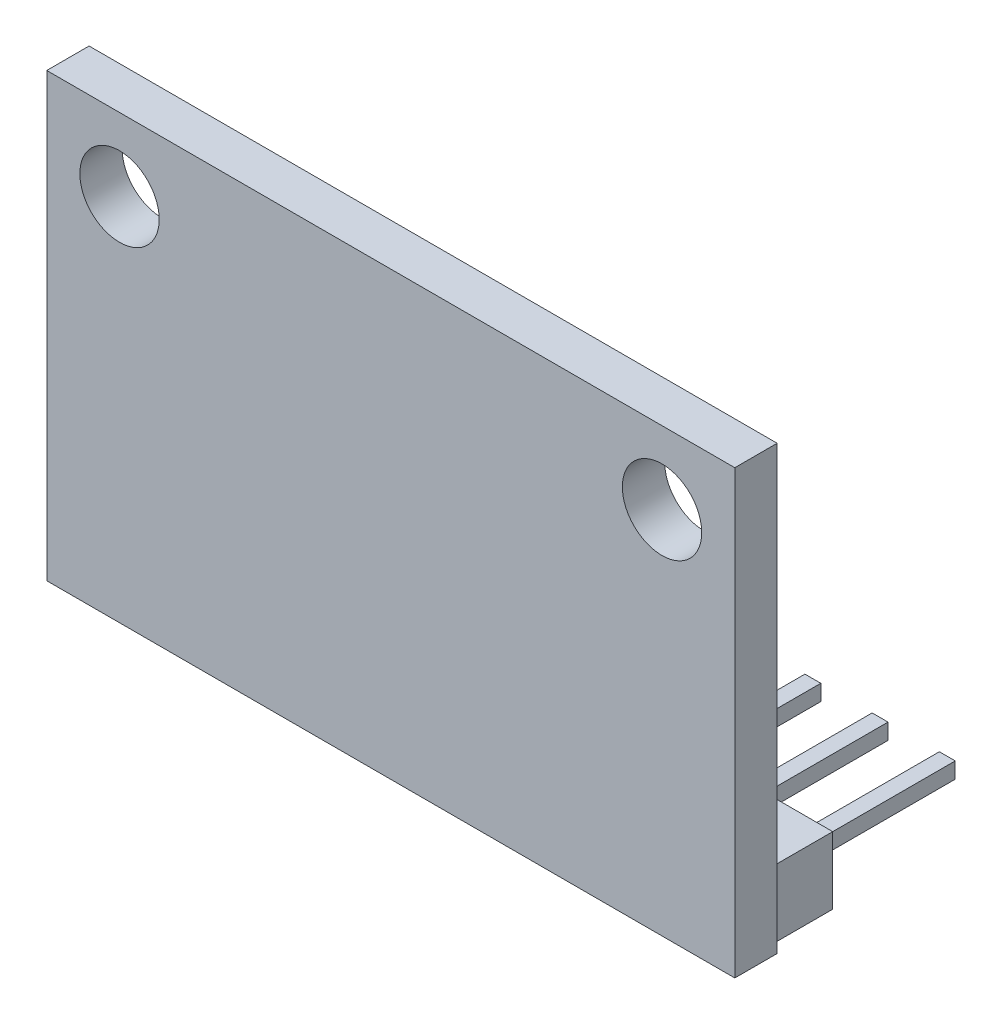
SolidWorks part; units mm, degrees
ref_plane "Ebene vorne" through (0, 0, 0) normal (0, 0, 1) x (1, 0, 0)
ref_plane "Ebene oben" through (0, 0, 0) normal (0, 1, 0) x (1, 0, 0)
ref_plane "Ebene rechts" through (0, 0, 0) normal (1, 0, 0) x (0, 0, -1)
sketch "Skizze1" plane through (0, 0, 0) normal (0, 0, 1) x (1, 0, 0)
  line L1 (-13, -8.35) -> (13, -8.35)
  line L2 (-13, -8.35) -> (-13, 8.35)
  line L3 (-13, 8.35) -> (13, 8.35)
  line L4 (13, -8.35) -> (13, 8.35)
  line L5 (-13, -8.35) -> (13, 8.35) construction
  line L6 (-13, 8.35) -> (13, -8.35) construction
  circle A0 centre (-10.25, 5.6) radius 1.5
  circle A1 centre (10.25, 5.6) radius 1.5
  point P0 (0, 0)
  point P10 (0, 0)
  dimension "D4" = 3
  dimension "D1" = 26
  dimension "D2" = 16.7
  dimension "D3" = 2.75
  dimension "D5" = 2.75
  dimension "D6" = 20.5
extrude "Aufsatz-Linear austragen1" add sketch "Skizze1" along normal blind 1.6
sketch "Skizze3" plane through (0, 0, 0) normal (0, 0, -1) x (-1, 0, 0)
  line L0 (-8.59, -7.28) -> (-8.59, -6.68) construction
  line L1 (-12.7, -8.25) -> (12.7, -8.25)
  line L2 (-12.7, -8.25) -> (-12.7, -5.71)
  line L3 (-12.7, -5.71) -> (12.7, -5.71)
  line L4 (12.7, -8.25) -> (12.7, -5.71)
  line L5 (-11.13, -7.28) -> (-11.73, -7.28) construction
  line L6 (-11.13, -7.28) -> (-11.13, -6.68) construction
  line L7 (-11.13, -6.68) -> (-11.73, -6.68) construction
  line L8 (-11.73, -7.28) -> (-11.73, -6.68) construction
  line L9 (-11.13, -7.28) -> (-11.73, -6.68) construction
  line L10 (-11.13, -6.68) -> (-11.73, -7.28) construction
  line L11 (-8.59, -7.28) -> (-9.19, -7.28) construction
  line L12 (-9.19, -7.28) -> (-9.19, -6.68) construction
  line L13 (-8.59, -6.68) -> (-9.19, -6.68) construction
  line L14 (-6.05, -7.28) -> (-6.05, -6.68) construction
  line L15 (-6.05, -7.28) -> (-6.65, -7.28) construction
  line L16 (-6.65, -7.28) -> (-6.65, -6.68) construction
  line L17 (-6.05, -6.68) -> (-6.65, -6.68) construction
  line L18 (-3.51, -7.28) -> (-3.51, -6.68) construction
  line L19 (-3.51, -7.28) -> (-4.11, -7.28) construction
  line L20 (-4.11, -7.28) -> (-4.11, -6.68) construction
  line L21 (-3.51, -6.68) -> (-4.11, -6.68) construction
  line L22 (-0.97, -7.28) -> (-0.97, -6.68) construction
  line L23 (-0.97, -7.28) -> (-1.57, -7.28) construction
  line L24 (-1.57, -7.28) -> (-1.57, -6.68) construction
  line L25 (-0.97, -6.68) -> (-1.57, -6.68) construction
  line L26 (1.57, -7.28) -> (1.57, -6.68) construction
  line L27 (1.57, -7.28) -> (0.97, -7.28) construction
  line L28 (0.97, -7.28) -> (0.97, -6.68) construction
  line L29 (1.57, -6.68) -> (0.97, -6.68) construction
  line L30 (4.11, -7.28) -> (4.11, -6.68) construction
  line L31 (4.11, -7.28) -> (3.51, -7.28) construction
  line L32 (3.51, -7.28) -> (3.51, -6.68) construction
  line L33 (4.11, -6.68) -> (3.51, -6.68) construction
  line L34 (6.65, -7.28) -> (6.65, -6.68) construction
  line L35 (6.65, -7.28) -> (6.05, -7.28) construction
  line L36 (6.05, -7.28) -> (6.05, -6.68) construction
  line L37 (6.65, -6.68) -> (6.05, -6.68) construction
  line L38 (9.19, -7.28) -> (9.19, -6.68) construction
  line L39 (9.19, -7.28) -> (8.59, -7.28) construction
  line L40 (8.59, -7.28) -> (8.59, -6.68) construction
  line L41 (9.19, -6.68) -> (8.59, -6.68) construction
  line L42 (11.73, -7.28) -> (11.73, -6.68) construction
  line L43 (11.73, -7.28) -> (11.13, -7.28) construction
  line L44 (11.13, -7.28) -> (11.13, -6.68) construction
  line L45 (11.73, -6.68) -> (11.13, -6.68) construction
  line L46 (-11.13, -7.28) -> (-8.59, -7.28) construction
  line L47 (11.43, -7.28) -> (11.43, -6.68) construction
  line L48 (0, -8.25) -> (0, 0) construction
  line L49 (13, -8.35) -> (-13, -8.35) construction
  point P4 (-11.43, -6.98)
  point P10 (-12.7, -6.98)
  dimension "D1" = 0.6
  dimension "D2" = 1.27
  dimension "D3" = 2.54
  dimension "D5" = 2.54
  dimension "D6" = 1.27
  dimension "D7" = 0.1
  dimension "D4" = 10
extrude "Aufsatz-Linear austragen2" add sketch "Skizze3" along normal blind 2.4 separate body
sketch "Skizze4" plane through (0, 0, -2.4) normal (0, 0, -1) x (-1, 0, 0)
  line L0 (-12.7, -5.71) -> (-12.7, -8.25) construction
  line L1 (-11.73, -7.28) -> (-11.13, -7.28)
  line L2 (-11.73, -7.28) -> (-11.73, -6.68)
  line L3 (-11.73, -6.68) -> (-11.13, -6.68)
  line L4 (-11.13, -7.28) -> (-11.13, -6.68)
  line L5 (-11.73, -7.28) -> (-11.13, -6.68) construction
  line L6 (-11.73, -6.68) -> (-11.13, -7.28) construction
  line L7 (-11.43, -6.98) -> (-12.7, -6.98) construction
  line L8 (-9.19, -7.28) -> (-9.19, -6.68)
  line L9 (-9.19, -7.28) -> (-8.59, -7.28)
  line L10 (-8.59, -7.28) -> (-8.59, -6.68)
  line L11 (-9.19, -6.68) -> (-8.59, -6.68)
  line L12 (-6.65, -7.28) -> (-6.65, -6.68)
  line L13 (-6.65, -7.28) -> (-6.05, -7.28)
  line L14 (-6.05, -7.28) -> (-6.05, -6.68)
  line L15 (-6.65, -6.68) -> (-6.05, -6.68)
  line L16 (-4.11, -7.28) -> (-4.11, -6.68)
  line L17 (-4.11, -7.28) -> (-3.51, -7.28)
  line L18 (-3.51, -7.28) -> (-3.51, -6.68)
  line L19 (-4.11, -6.68) -> (-3.51, -6.68)
  line L20 (-1.57, -7.28) -> (-1.57, -6.68)
  line L21 (-1.57, -7.28) -> (-0.97, -7.28)
  line L22 (-0.97, -7.28) -> (-0.97, -6.68)
  line L23 (-1.57, -6.68) -> (-0.97, -6.68)
  line L24 (0.97, -7.28) -> (0.97, -6.68)
  line L25 (0.97, -7.28) -> (1.57, -7.28)
  line L26 (1.57, -7.28) -> (1.57, -6.68)
  line L27 (0.97, -6.68) -> (1.57, -6.68)
  line L28 (3.51, -7.28) -> (3.51, -6.68)
  line L29 (3.51, -7.28) -> (4.11, -7.28)
  line L30 (4.11, -7.28) -> (4.11, -6.68)
  line L31 (3.51, -6.68) -> (4.11, -6.68)
  line L32 (6.05, -7.28) -> (6.05, -6.68)
  line L33 (6.05, -7.28) -> (6.65, -7.28)
  line L34 (6.65, -7.28) -> (6.65, -6.68)
  line L35 (6.05, -6.68) -> (6.65, -6.68)
  line L36 (8.59, -7.28) -> (8.59, -6.68)
  line L37 (8.59, -7.28) -> (9.19, -7.28)
  line L38 (9.19, -7.28) -> (9.19, -6.68)
  line L39 (8.59, -6.68) -> (9.19, -6.68)
  line L40 (11.13, -7.28) -> (11.13, -6.68)
  line L41 (11.13, -7.28) -> (11.73, -7.28)
  line L42 (11.73, -7.28) -> (11.73, -6.68)
  line L43 (11.13, -6.68) -> (11.73, -6.68)
  line L44 (-11.73, -7.28) -> (-9.19, -7.28) construction
  point P0 (-11.43, -6.98)
  dimension "D1" = 0.6
  dimension "D2" = 1.27
  dimension "D4" = 2.54
  dimension "D3" = 10
extrude "Aufsatz-Linear austragen3" add sketch "Skizze4" along normal blind 5.6 separate body
